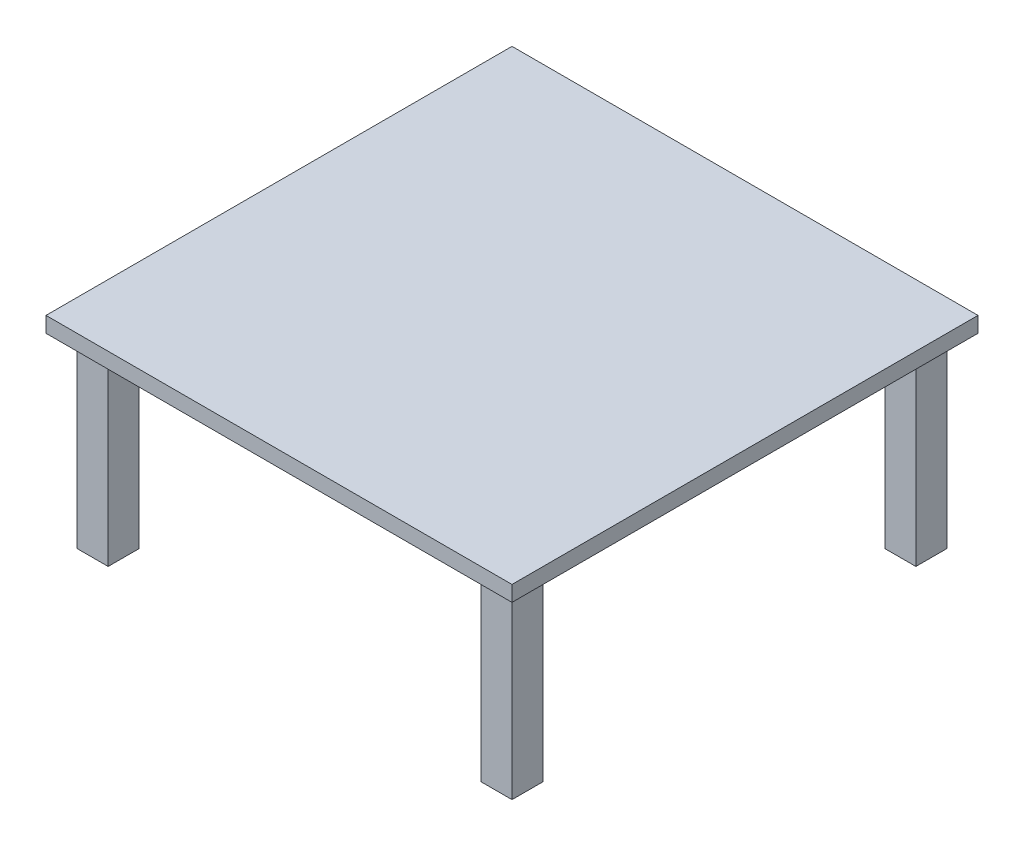
SolidWorks part; units mm, degrees
ref_plane "前基準面" through (0, 0, 0) normal (0, 0, 1) x (1, 0, 0)
ref_plane "上基準面" through (0, 0, 0) normal (0, 1, 0) x (1, 0, 0)
ref_plane "右基準面" through (0, 0, 0) normal (1, 0, 0) x (0, 0, -1)
sketch "草圖2" plane through (0, 0, 0) normal (0, 1, 0) x (1, 0, 0)
  line L1 (-15, 15) -> (15, 15)
  line L2 (-15, 15) -> (-15, -15)
  line L3 (-15, -15) -> (15, -15)
  line L4 (15, 15) -> (15, -15)
  line L5 (-15, 15) -> (15, -15) construction
  line L6 (-15, -15) -> (15, 15) construction
  point P0 (0, 0)
  dimension "D1" = 30
  dimension "D2" = 30
extrude "填料-伸長1" add sketch "草圖2" along normal blind 1
sketch "草圖3" plane through (0, 0, 0) normal (0, -1, 0) x (1, 0, 0)
  line L0 (-15, 15) -> (15, 15) construction
  line L1 (-14, 14) -> (-12, 14)
  line L2 (-14, 14) -> (-14, 12)
  line L3 (-14, 12) -> (-12, 12)
  line L4 (-12, 14) -> (-12, 12)
  line L5 (-15, -15) -> (-15, 15) construction
  line L6 (0, 0) -> (0, 15) construction
  line L7 (0, 0) -> (-15, 0) construction
  line L8 (14, 12) -> (12, 12)
  line L9 (12, 14) -> (12, 12)
  line L10 (14, 14) -> (12, 14)
  line L11 (14, 14) -> (14, 12)
  line L12 (14, -14) -> (14, -12)
  line L13 (14, -14) -> (12, -14)
  line L14 (12, -14) -> (12, -12)
  line L15 (14, -12) -> (12, -12)
  line L16 (-14, -12) -> (-12, -12)
  line L17 (-12, -14) -> (-12, -12)
  line L18 (-14, -14) -> (-12, -14)
  line L19 (-14, -14) -> (-14, -12)
  dimension "D1" = 2
  dimension "D2" = 2
  dimension "D3" = 1
  dimension "D4" = 1
extrude "填料-伸長2" add sketch "草圖3" along normal blind 12
